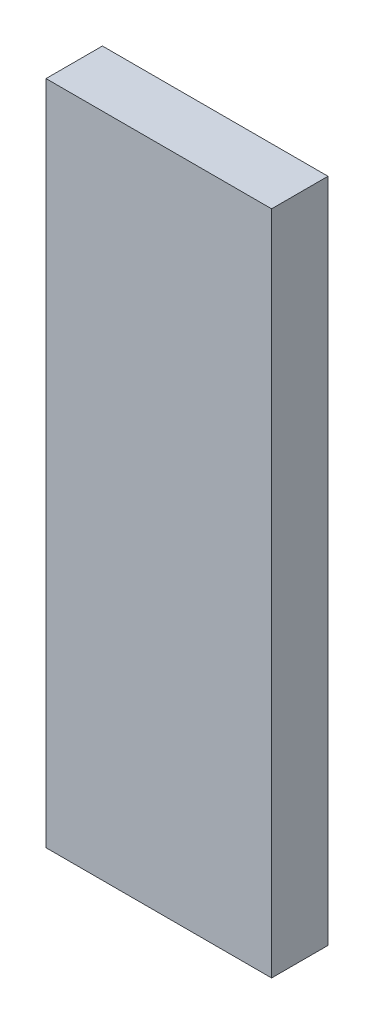
SolidWorks part; units mm, degrees
ref_plane "Front Plane" through (0, 0, 0) normal (0, 0, 1) x (1, 0, 0)
ref_plane "Top Plane" through (0, 0, 0) normal (0, 1, 0) x (1, 0, 0)
ref_plane "Right Plane" through (0, 0, 0) normal (1, 0, 0) x (0, 0, -1)
sketch "Sketch2" plane through (0, 0, 0) normal (0, 0, 1) x (1, 0, 0)
  line L1 (0, 0) -> (25.4, 0)
  line L2 (0, 0) -> (0, 75)
  line L3 (0, 75) -> (25.4, 75)
  line L4 (25.4, 0) -> (25.4, 75)
  dimension "D1" = 25.4
  dimension "D2" = 75
extrude "Boss-Extrude1" add sketch "Sketch2" along normal blind 6.35
equation "\"Wheel Thickness\"= 1in"
equation "\"Wheel Diameter\"= 3in"
equation "\"Motor Rear Diameter\" = 36.2mm"
equation "\"Motor Front Diameter\" = 12mm"
equation "\"Material Thickness\" = .25in"
equation "\"Wheel Cutout Diameter\"= 2cm"
equation "\"Motor Mount Tab Thickness\" = 100mm"
equation "\"Motor Mount Tab Height\" = 40mm"
equation "\"Motor Shaft Diameter\" = 3mm"
equation "\"Wheel Radius Clearance\" = 5mm"
equation "\"Wheel Cutout Width\" = 1.5in"
equation "\"Base Diameter\" = 10in"
equation "\"Wheel Mount Distance\" = 5mm"
equation "\"Motor Mount Distance\" = 50mm"
equation "\"Motor Cutout Length\" = 6in"
equation "\"Motor Cutout Height\" = 2in "
equation "\"Rod Diameter\" = 3/8in"
equation "\"Rod Length\" = 1.5in"
equation "\"Barrel Front Length\" = 1.8in"
equation "\"Barrerl Rear Length\" = 5in "
equation "\"Barrel Fillet Radius\" = 1in "
equation "\"Barrel Angle\" = 20deg"
equation "\"Barrel Diameter\" = 50mm"
equation "\"Barrel Shell Width\" = 2mm"
equation "\"Second Level Diameter\" = 10in"
equation "\"Ball Diameter\" = 40mm"
equation "\"Third Level Length\" = 9in"
equation "\"Third Level Height\" = 9in"
equation "\"Barrel Tab Clearance\" = 5mm"
equation "\"Barrel Tab Distance Away\" = 2mm"
equation "\"Hole Distance Apart\" = 2.8in"
equation "\"Barrel Tab Distance\"= 1.5in "
equation "\"Third Level Rod Distance\" = .5in"
equation " \"Second Rod Diameter\" = 3/8in"
equation "\"Second Rod Length\" = 3.88in"
equation "\"Bumper Wheel Clearance\" = 1.2in"
equation "\"Servo Tab Height\" = 4in"
equation "\"Servo Tab Width\" = 2in"
equation "\"Servo Tab Hole Horizontal Distance\" = 1in"
equation "\"Servo Tab Hole Vertical Distance\" = 1.5in "
equation "\"Servo Hole Vertical Distance\" = 3in"
equation "\"Servo Hole Diameter\" = 1/4in"
equation "\"Servo Hole Shaft Length\" = 1.45in"
equation "\"Third Rod Length\" = 3.83in"
equation "\"Third Rod Diameter\" = 3/8in"
equation "\"Third Rod Radius Distance\" = 1.5in"
equation "\"Third Rod Angle Distance\" = 20deg"
equation "\"Fourth Level Diameter\" = 3.5in"
equation "\"Skid Length\" = 2in"
equation "\"Skid Width\" = 1.5in"
equation "\"Skid Clearance\" = 3mm"
equation "\"Skid Cut Distance\" = .25in"
equation "\"Skid Fillet Radius\" = .5in"
equation "\"D2@Sketch2\"=(\"Motor Mount Tab Thickness\")-(\"Motor Mount Tab Thickness\"/4)"
equation "\"D1@Boss-Extrude1\"=\"Material Thickness\""
equation "\"Motor Mount Slab Distance\" = 1in"
equation "\"D1@Sketch2\"=\"Motor Mount Slab Distance\""
